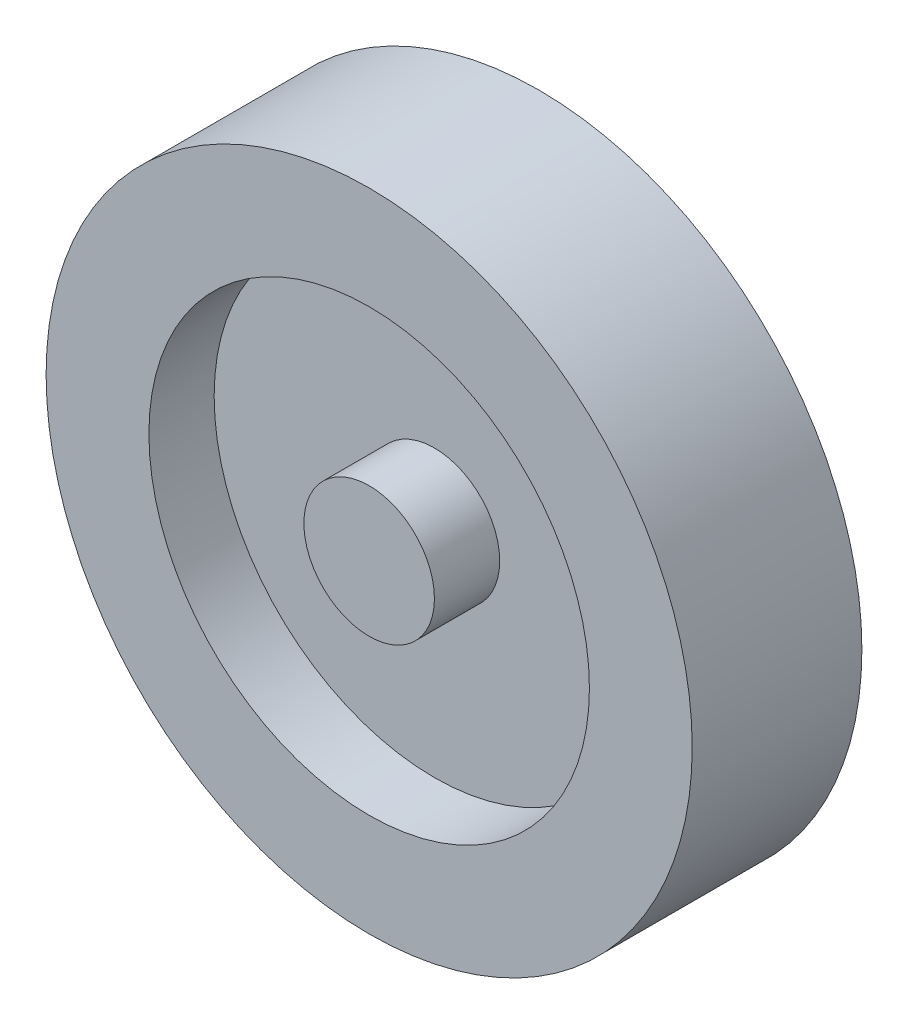
SolidWorks part; units mm, degrees
ref_plane "Plan de face" through (0, 0, 0) normal (0, 0, 1) x (1, 0, 0)
ref_plane "Plan de dessus" through (0, 0, 0) normal (0, 1, 0) x (1, 0, 0)
ref_plane "Plan de droite" through (0, 0, 0) normal (1, 0, 0) x (0, 0, -1)
sketch "Esquisse1" plane through (0, 0, 0) normal (0, 0, 1) x (1, 0, 0)
  circle A0 centre (0, 0) radius 49.5
  dimension "D1" = 99
extrude "Boss.-Extru.2" add sketch "Esquisse1" along normal blind 13 contours A0
sketch "Esquisse4" plane through (0, 0, 0) normal (0, 0, 1) x (1, 0, 0)
sketch "Esquisse5" plane through (0, 0, 13) normal (0, 0, 1) x (1, 0, 0)
  circle A0 centre (0, 0) radius 10
  circle A1 centre (0, 0) radius 33.75
  dimension "D1" = 20
  dimension "D2" = 67.5
extrude "Enlèv. mat.-Extru.1" cut sketch "Esquisse5" against normal blind 10
mirror "Symétrie6" about plane through (0, 0, 0) normal (0, 0, 1) of bodies 108
sketch "Esquisse12" plane through (0, 0, -13) normal (0, 0, -1) x (-1, 0, 0)
  circle A0 centre (0, 0) radius 10
extrude "Boss.-Extru.3" add sketch "Esquisse12" along normal blind 18.5
sketch "Esquisse13" plane through (0, 0, -31.5) normal (0, 0, -1) x (-1, 0, 0)
  circle A0 centre (0, 0) radius 3
  dimension "D1" = 6
extrude "Enlèv. mat.-Extru.2" cut sketch "Esquisse13" against normal blind 10 contours A0
